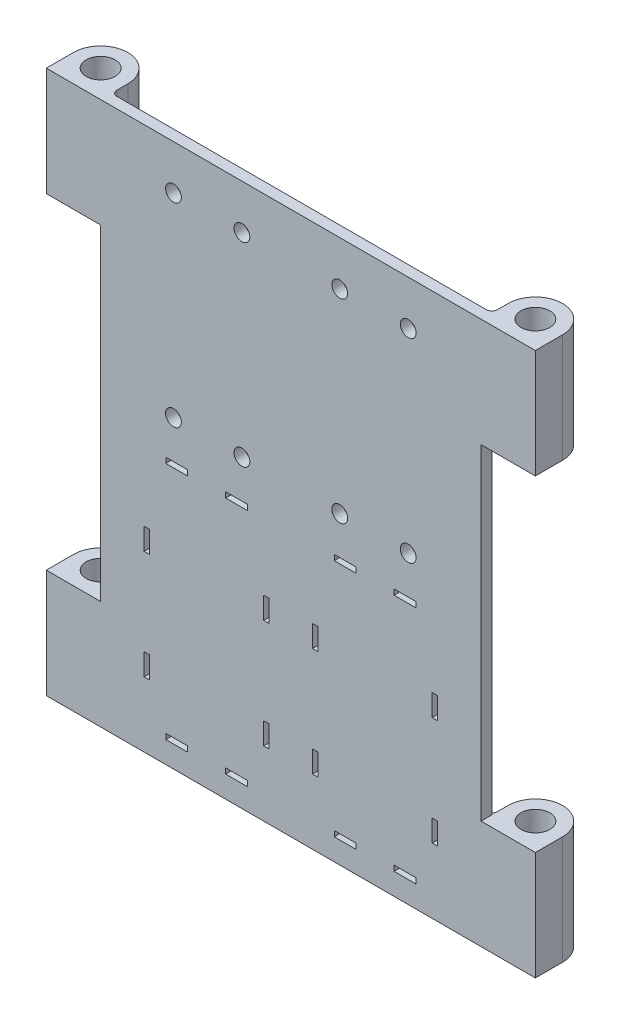
SolidWorks part; units mm, degrees
ref_plane "Front Plane" through (0, 0, 0) normal (0, 0, 1) x (1, 0, 0)
ref_plane "Top Plane" through (0, 0, 0) normal (0, 1, 0) x (1, 0, 0)
ref_plane "Right Plane" through (0, 0, 0) normal (1, 0, 0) x (0, 0, -1)
sketch "Sketch1" plane through (0, 0, 0) normal (0, 1, 0) x (1, 0, 0)
  line L0 (0, 0) -> (0, -6.35) construction
  line L1 (0, -6.35) -> (57.15, -6.35)
  line L2 (0, -6.35) -> (-57.15, -6.35)
  line L3 (57.15, -6.35) -> (57.15, 0)
  line L4 (-57.15, -6.35) -> (-57.15, 0)
  line L5 (57.15, 0) -> (50.8, 0) construction
  line L6 (-57.15, 0) -> (-50.8, 0) construction
  line L7 (-44.45, 0) -> (-44.45, -3.81)
  line L8 (-44.45, -3.81) -> (44.45, -3.81)
  line L9 (44.45, -3.81) -> (44.45, 0)
  arc A0 (57.15, 0) -> (44.45, 0) centre (50.8, 0) ccw
  arc A1 (-57.15, 0) -> (-44.45, 0) centre (-50.8, 0) cw
  dimension "D1" = 6.35
  dimension "D2" = 57.15
  dimension "D3" = 57.15
  dimension "D4" = 6.35
  dimension "D5" = 6.35
  dimension "D6" = 6.35
  dimension "D7" = 6.35
  dimension "D8" = 3.81
  dimension "D10" = 88.9
extrude "Boss-Extrude1" add sketch "Sketch1" along normal mid plane 127
sketch "Sketch3" plane through (0, 0, 3.81) normal (0, 0, -1) x (-1, 0, 0)
  line L0 (0, 0) -> (0, -2.54) construction
  line L1 (0, -2.54) -> (6.35, -2.54) construction
  line L2 (6.35, -2.54) -> (6.35, -17.78) construction
  line L4 (6.35, -17.78) -> (5.08, -17.78)
  line L5 (6.35, -17.78) -> (6.35, -22.86)
  line L6 (6.35, -22.86) -> (5.08, -22.86)
  line L7 (5.08, -17.78) -> (5.08, -22.86)
  dimension "D1" = 2.54
  dimension "D2" = 15.24
  dimension "D3" = 5.08
  dimension "D4" = 1.27
  dimension "D5" = 6.35
extrude "Cut-Extrude2" cut sketch "Sketch3" against normal through all
pattern_linear "LPattern1" count 2 spacing 25.4 along (0, -1, 0) count 2 spacing 27.94 along (-1, 0, 0) of "Cut-Extrude2"
mirror "Mirror1" about plane through (0, 0, 0) normal (1, 0, 0) of "LPattern1", "Cut-Extrude2"
sketch "Sketch5" plane through (0, 0, 3.81) normal (0, 0, -1) x (-1, 0, 0)
  line L0 (6.35, -2.54) -> (10.16, -2.54) construction
  line L2 (10.16, -2.54) -> (15.24, -2.54)
  line L3 (10.16, -2.54) -> (10.16, -1.27)
  line L4 (10.16, -1.27) -> (15.24, -1.27)
  line L5 (15.24, -2.54) -> (15.24, -1.27)
  dimension "D1" = 3.81
  dimension "D2" = 5.08
  dimension "D3" = 1.27
extrude "Cut-Extrude3" cut sketch "Sketch5" against normal through all
pattern_linear "LPattern2" count 2 spacing 13.97 along (-1, 0, 0) count 2 spacing 55.88 along (0, -1, 0) of "Cut-Extrude3"
mirror "Mirror2" about plane through (0, 0, 0) normal (1, 0, 0) of "LPattern2", "Cut-Extrude3"
sketch "Sketch6" plane through (0, 0, 3.81) normal (0, 0, -1) x (-1, 0, 0)
  line L0 (0, 0) -> (0, 7.62) construction
  line L1 (0, 7.62) -> (11.43, 7.62) construction
  dimension "D1" = 7.62
  dimension "D2" = 11.43
hole_wizard "Ø1.0mm Dowel Hole1" positions "Sketch7" profile "Sketch8" hole size "Ø1.0" standard "ANSI Metric" end condition through all
sketch "Sketch7" plane through (0, 0, 0) normal (0, 0, 1) x (1, 0, 0)
  point P0 (-11.43, 7.62)
sketch "Sketch8" plane through (-11.43, 7.62, 0) normal (1, 0, 0) x (0, 1, 0)
  line L0 (0, 0) -> (0, 6.35)
  line L1 (0, 6.35) -> (1.85, 6.35)
  line L2 (1.85, 6.35) -> (1.85, 0)
  line L5 (1.85, 0) -> (0, 0)
  line L11 (0, -6.35) -> (0, 107.95) construction
  dimension "Thru Hole Dia." = 3.7
  dimension "Thru Hole Depth" = 6.35
pattern_linear "LPattern3" count 2 spacing 16.002 along (-1, 0, 0) count 2 spacing 45.466 along (0, 1, 0) of "Ø1.0mm Dowel Hole1"
mirror "Mirror3" about plane through (0, 0, 0) normal (1, 0, 0) of "LPattern3", "Ø1.0mm Dowel Hole1"
hole_wizard "1/4 Clearance Hole1" positions "Sketch13" profile "Sketch15" hole size "1/4" standard "ANSI Inch" end condition through all
sketch "Sketch13" plane through (0, 63.5, 0) normal (0, 1, 0) x (1, 0, 0)
  point P0 (-50.8, 0)
sketch "Sketch15" plane through (-50.8, 63.5, 0) normal (1, 0, 0) x (0, 0, 1)
  line L0 (0, 0) -> (0, 127)
  line L1 (0, 127) -> (3.3782, 127)
  line L2 (3.3782, 127) -> (3.3782, 0)
  line L5 (3.3782, 0) -> (0, 0)
  line L11 (0, -6.35) -> (0, 107.95) construction
  dimension "Thru Hole Dia." = 6.7564
  dimension "Thru Hole Depth" = 127
mirror "Mirror4" about plane through (0, 0, 0) normal (1, 0, 0) of "1/4 Clearance Hole1"
sketch "Sketch16" plane through (0, 0, 0) normal (0, 1, 0) x (1, 0, 0)
  line L0 (-57.15, 0) -> (-57.15, -6.35)
  line L1 (-44.45, 0) -> (-44.45, -6.35)
  line L2 (0, -6.35) -> (-57.15, -6.35) construction
  line L3 (-44.45, -6.35) -> (-57.15, -6.35)
  arc A0 (-57.15, 0) -> (-44.45, 0) centre (-50.8, 0) cw
  arc A1 (-44.45, 0) -> (-57.15, 0) centre (-50.8, 0) ccw construction
extrude "Cut-Extrude4" cut sketch "Sketch16" against normal mid plane 76.2
mirror "Mirror5" about plane through (0, 0, 0) normal (1, 0, 0) of "Cut-Extrude4"
fillet "Fillet1" radius 1.27 2 edges at (-44.45, 50.8, 3.81) (-44.45, -50.8, 3.81)
fillet "Fillet2" radius 1.27 2 edges at (44.45, 50.8, 3.81) (44.45, -50.8, 3.81)
